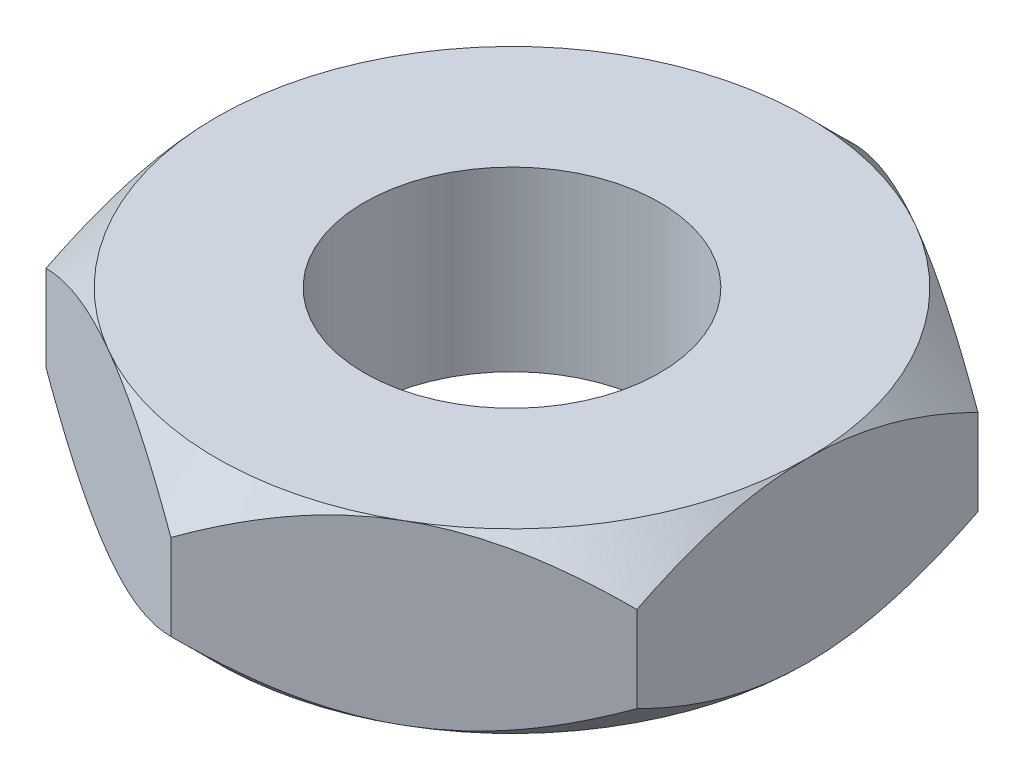
SolidWorks part; units mm, degrees
material "Plain Carbon Steel"
ref_plane "Front Plane" through (0, 0, 0) normal (0, 0, 1) x (1, 0, 0)
ref_plane "Top Plane" through (0, 0, 0) normal (0, 1, 0) x (1, 0, 0)
ref_plane "Right Plane" through (0, 0, 0) normal (1, 0, 0) x (0, 0, -1)
sketch "Sketch1" plane through (0, 0, 0) normal (0, 1, 0) x (1, 0, 0)
  line L1 (0, 2.3094) -> (-2, 1.1547)
  line L2 (-2, 1.1547) -> (-2, -1.1547)
  line L3 (-2, -1.1547) -> (0, -2.3094)
  line L4 (0, -2.3094) -> (2, -1.1547)
  line L5 (2, -1.1547) -> (2, 1.1547)
  line L6 (2, 1.1547) -> (0, 2.3094)
  circle A0 centre (0, 0) radius 1
  circle A1 centre (0, 0) radius 2 construction
  dimension "D1" = 2
  dimension "D2" = 4
extrude "Boss-Extrude1" add sketch "Sketch1" along normal mid plane 1.2
sketch "Sketch2" plane through (0, 0.6, 0) normal (0, 1, 0) x (1, 0, 0)
  line L0 (-2, 1.1547) -> (-2, -1.1547) construction
  circle A0 centre (0, 0) radius 2
sketch "Sketch3" plane through (0, 0, 0) normal (0, 0, 1) x (1, 0, 0)
  line L0 (-2.5, 0.1) -> (-2, 0.6)
  line L3 (-2, 0.6) -> (-2.5, 0.6)
  line L4 (-2.5, 0.6) -> (-2.5, 0.1)
  dimension "D1" = 0.5
  dimension "D2" = 0.5
sweep "Cut-Sweep1" cut profiles "Sketch3" path "Sketch2"
mirror "Mirror1" about plane through (0, 0, 0) normal (0, 1, 0) of "Cut-Sweep1"
